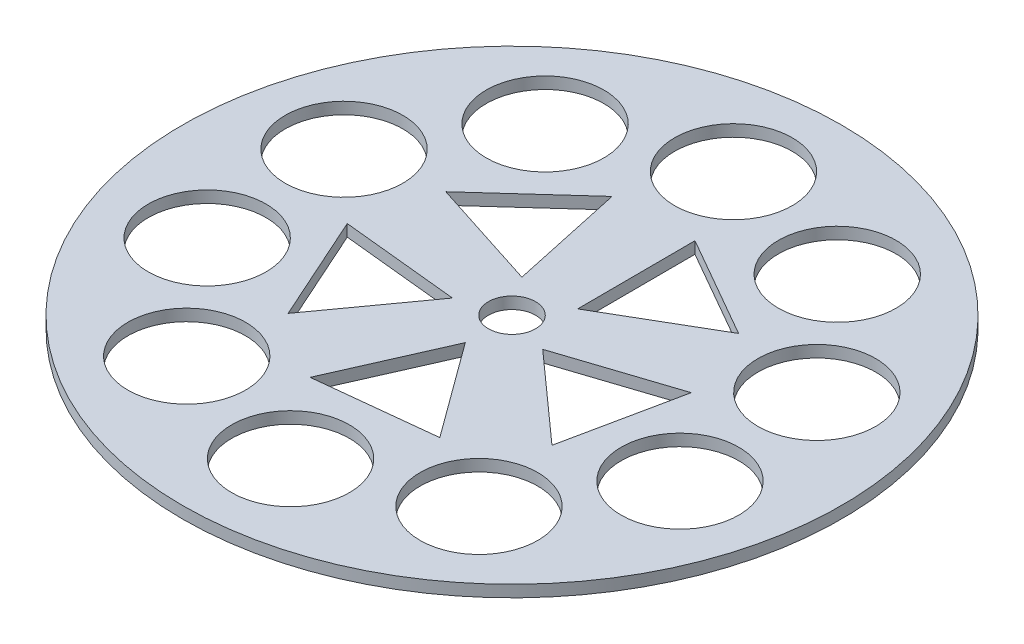
SolidWorks part; units mm, degrees
ref_plane "Front Plane" through (0, 0, 0) normal (0, 0, 1) x (1, 0, 0)
ref_plane "Top Plane" through (0, 0, 0) normal (0, 1, 0) x (1, 0, 0)
ref_plane "Right Plane" through (0, 0, 0) normal (1, 0, 0) x (0, 0, -1)
sketch "Sketch1" plane through (0, 0, 0) normal (0, 1, 0) x (1, 0, 0)
  line L0 (84.5454, 12.1714) -> (24.2195, -7.6536)
  line L1 (14.5503, 84.1686) -> (14.7633, 20.669)
  line L2 (14.7633, 20.669) -> (69.6491, 52.6033)
  line L3 (69.6491, 52.6033) -> (14.5503, 84.1686)
  line L4 (71.5514, -49.9849) -> (84.5454, 12.1714)
  line L5 (24.2195, -7.6536) -> (71.5514, -49.9849)
  line L6 (37.7017, -76.6463) -> (0.2052, -25.3992)
  line L7 (-25.4279, -83.4956) -> (37.7017, -76.6463)
  line L8 (0.2052, -25.3992) -> (-25.4279, -83.4956)
  line L9 (-61.2445, -59.5414) -> (-24.0926, -8.0439)
  line L10 (-87.2667, -1.6182) -> (-61.2445, -59.5414)
  line L11 (-24.0926, -8.0439) -> (-87.2667, -1.6182)
  line L12 (-75.5528, 39.8476) -> (-15.0953, 20.4278)
  line L13 (-28.5059, 82.4955) -> (-75.5528, 39.8476)
  line L14 (-15.0953, 20.4278) -> (-28.5059, 82.4955)
  circle A0 centre (0, 0) radius 177.8
  circle A1 centre (-80.4419, 98.2757) radius 31.75
  circle A2 centre (-7.3138, 126.7892) radius 31.75
  circle A3 centre (68.6078, 106.8736) radius 31.75
  circle A4 centre (118.3236, 46.1359) radius 31.75
  circle A5 centre (122.8438, -32.2241) radius 31.75
  circle A6 centre (80.4419, -98.2757) radius 31.75
  circle A7 centre (7.3138, -126.7892) radius 31.75
  circle A8 centre (-68.6078, -106.8736) radius 31.75
  circle A9 centre (-118.3236, -46.1359) radius 31.75
  circle A10 centre (-122.8438, 32.2241) radius 31.75
  circle A11 centre (0, 0) radius 12.7
  circle A12 centre (32.9875, 52.4803) radius 18.3309 construction
  point P26 (0, 0)
  point P45 (0, 0)
  dimension "D1" = 355.6
  dimension "D2" = 63.5
  dimension "D5" = 25.4
  dimension "D3" = 127
  dimension "D6" = 63.5
  dimension "D7" = 70
  dimension "D9" = 25.4
  dimension "D4" = 10
  dimension "D8" = 5
extrude "Boss-Extrude1" add sketch "Sketch1" along normal blind 6.35
